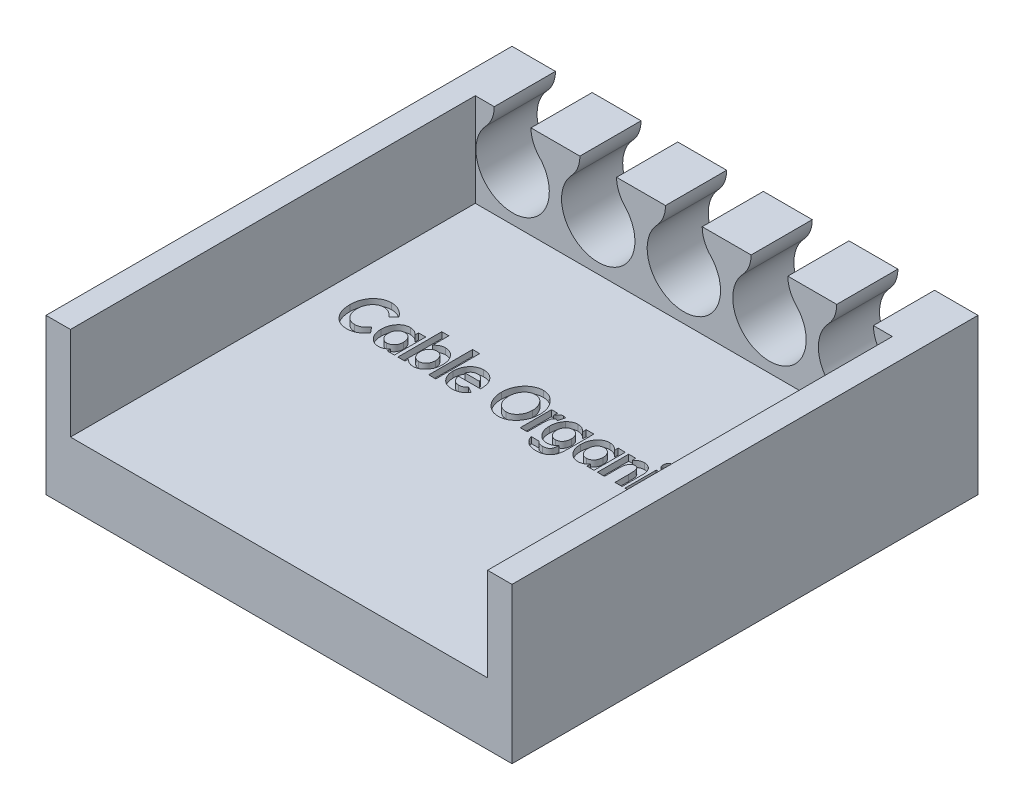
SolidWorks part; units mm, degrees
ref_plane "Front Plane" through (0, 0, 0) normal (0, 0, 1) x (1, 0, 0)
ref_plane "Top Plane" through (0, 0, 0) normal (0, 1, 0) x (1, 0, 0)
ref_plane "Right Plane" through (0, 0, 0) normal (1, 0, 0) x (0, 0, -1)
sketch "Sketch1" plane through (0, 0, 0) normal (0, 1, 0) x (1, 0, 0)
  line L1 (0.0256, -0.0238) -> (0, -0.0238)
  line L2 (0.0256, -0.0238) -> (0.0256, 0)
  line L3 (0.0256, 0) -> (0, 0)
  line L4 (0, -0.0238) -> (0, 0)
  line L5 (-19.05, -19.05) -> (19.05, -19.05)
  line L6 (-19.05, -19.05) -> (-19.05, 19.05)
  line L7 (-19.05, 19.05) -> (19.05, 19.05)
  line L8 (19.05, -19.05) -> (19.05, 19.05)
  line L9 (-19.05, -19.05) -> (19.05, 19.05) construction
  line L10 (-19.05, 19.05) -> (19.05, -19.05) construction
  dimension "D1" = 38.1
  dimension "D2" = 38.1
extrude "Boss-Extrude1" add sketch "Sketch1" along normal blind 12.7 contours L6 L5 L8 L7
sketch "Sketch2" plane through (0, 12.7, 0) normal (0, 1, 0) x (1, 0, 0)
  line L0 (-19.05, -19.05) -> (19.05, -19.05) construction
  line L1 (-17.05, 14.05) -> (17.05, 14.05)
  line L2 (-17.05, 14.05) -> (-17.05, -19.05)
  line L3 (-17.05, -19.05) -> (17.05, -19.05)
  line L4 (17.05, 14.05) -> (17.05, -19.05)
  line L5 (-19.05, -19.05) -> (-19.05, 19.05) construction
  line L6 (19.05, -19.05) -> (19.05, 19.05) construction
  line L7 (-19.05, 19.05) -> (19.05, 19.05) construction
  dimension "D1" = 2
  dimension "D2" = 2
  dimension "D3" = 5
extrude "Cut-Extrude1" cut sketch "Sketch2" against normal blind 7.62 contours L2 L1 L4 L3
sketch "Sketch3" plane through (0, 0, -19.05) normal (0, 0, -1) x (-1, 0, 0)
  line L0 (0, 0) -> (0, 12.7) construction
  line L1 (19.05, 12.7) -> (-19.05, 12.7) construction
  line L2 (0, 12.7) -> (-12.5, 12.7)
  line L4 (-12.5, 12.7) -> (-15.5, 12.7)
  line L5 (-5.5, 12.7) -> (-8.5, 12.7)
  line L6 (1.5, 12.7) -> (-1.5, 12.7)
  line L7 (8.5, 12.7) -> (5.5, 12.7)
  line L8 (15.5, 12.7) -> (12.5, 12.7)
  arc A0 (-12.5, 12.7) -> (-11.8182, 10.9841) centre (-10, 12.7) ccw
  arc A1 (-15.5, 12.7) -> (-16.1818, 10.9841) centre (-18, 12.7) cw
  arc A2 (-11.8182, 10.9841) -> (-16.1818, 10.9841) centre (-14, 8.9251) cw
  arc A3 (-5.5, 12.7) -> (-4.8182, 10.9841) centre (-3, 12.7) ccw
  arc A4 (-4.8182, 10.9841) -> (-9.1818, 10.9841) centre (-7, 8.9251) cw
  arc A5 (-8.5, 12.7) -> (-9.1818, 10.9841) centre (-11, 12.7) cw
  arc A6 (1.5, 12.7) -> (2.1818, 10.9841) centre (4, 12.7) ccw
  arc A7 (2.1818, 10.9841) -> (-2.1818, 10.9841) centre (0, 8.9251) cw
  arc A8 (-1.5, 12.7) -> (-2.1818, 10.9841) centre (-4, 12.7) cw
  arc A9 (8.5, 12.7) -> (9.1818, 10.9841) centre (11, 12.7) ccw
  arc A10 (9.1818, 10.9841) -> (4.8182, 10.9841) centre (7, 8.9251) cw
  arc A11 (5.5, 12.7) -> (4.8182, 10.9841) centre (3, 12.7) cw
  arc A12 (15.5, 12.7) -> (16.1818, 10.9841) centre (18, 12.7) ccw
  arc A13 (16.1818, 10.9841) -> (11.8182, 10.9841) centre (14, 8.9251) cw
  arc A14 (12.5, 12.7) -> (11.8182, 10.9841) centre (10, 12.7) cw
  point P12 (-14, 12.7)
  dimension "D3" = 3
  dimension "D4" = 2.5
  dimension "D5" = 2.5
  dimension "D1" = 3
  dimension "D2" = 12.5
  dimension "D6" = 5
extrude "Cut-Extrude2" cut sketch "Sketch3" against normal through all contours A0 A2 A1 L4 | L5 A5 A4 A3 | L6 A8 A7 A6 | L7 A11 A10 A9 | L8 A14 A13 A12
sketch "Sketch5" plane through (0, 5.08, 0) normal (0, 1, 0) x (1, 0, 0)
  line L0 (17.05, 0) -> (-17.05, 0) construction
  line L1 (17.05, 14.05) -> (17.05, -19.05) construction
  line L2 (-17.05, 14.05) -> (-17.05, -19.05) construction
  text T0 "<b>Cable Organizer</b>" font "Century Gothic" height 3.5
extrude "Cut-Extrude3" cut sketch "Sketch5" against normal blind 0.5
